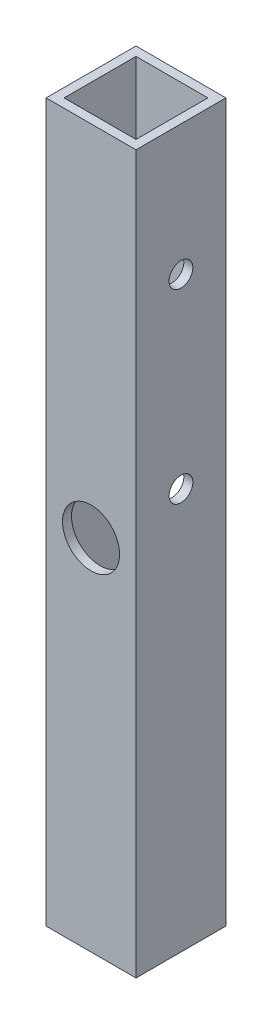
SolidWorks part; units mm, degrees
material "5052-H34"
ref_plane "Front Plane" through (0, 0, 0) normal (0, 0, 1) x (1, 0, 0)
ref_plane "Top Plane" through (0, 0, 0) normal (0, 1, 0) x (1, 0, 0)
ref_plane "Right Plane" through (0, 0, 0) normal (1, 0, 0) x (0, 0, -1)
sketch "Sketch1" plane through (0, 0, 0) normal (0, 0, 1) x (1, 0, 0)
  line L1 (-10, -79.8) -> (10, -79.8)
  line L2 (-10, -79.8) -> (-10, 79.8)
  line L3 (-10, 79.8) -> (10, 79.8)
  line L4 (10, -79.8) -> (10, 79.8)
  point P4 (10, 0)
  point P6 (0, 79.8)
  dimension "D1" = 159.6
  dimension "D2" = 20
extrude "Boss-Extrude1" add sketch "Sketch1" along normal blind 2
ref_plane "Plane1" through (-10, 79.8, 2) normal (0, -1, 0) x (-1, 0, 0)
sketch "Sketch4" plane through (0, 79.8, 0) normal (0, 1, 0) x (1, 0, 0)
  line L0 (10, -2) -> (10, 0) construction
  line L2 (-10, -2) -> (-10, -20)
  line L3 (-10, -20) -> (10, -20)
  line L4 (10, -2) -> (10, -20)
  line L5 (10, 0) -> (-10, 0) construction
  line L6 (10, -2) -> (-10, -2) construction
  line L7 (-8, -2) -> (8, -2)
  line L8 (-8, -2) -> (-8, -18)
  line L9 (-8, -18) -> (8, -18)
  line L10 (8, -2) -> (8, -18)
  line L11 (-10, -2) -> (-8, -2)
  line L12 (8, -2) -> (10, -2)
  line M9 (-10, -2) -> (10, -2)
  dimension "D1" = 0
  dimension "D2" = 20
  dimension "D3" = 2
  dimension "D4" = 2
  dimension "D5" = 2
extrude "Boss-Extrude2" add sketch "Sketch4" against normal up to surface (159.6 mm away) contours L10 L9 L8 L2 L3 L4 M9 up to face at (0, -79.8, 1)
sketch "Sketch3" plane through (0, 0, 0) normal (0, 0, -1) x (-1, 0, 0)
  line L0 (0, 79.8) -> (0, -79.8) construction
  line L1 (-33.89, 79.8) -> (53.89, 79.8) construction
  line L2 (10, -79.8) -> (-10, -79.8) construction
  circle A0 centre (0, 0) radius 6.35
  dimension "D1" = 12.7
extrude "Cut-Extrude1" cut sketch "Sketch3" against normal through all both and the other way through all
sketch "Sketch5" plane through (10, 0, 0) normal (1, 0, 0) x (0, 0, -1)
  circle A0 centre (-10, 50.8) radius 2.65 construction
  circle A1 centre (-10, 50.8) radius 2.65
  circle A2 centre (-10, 9.4343) radius 2.65
  circle A3 centre (-10, 9.4343) radius 2.65 construction
extrude "Cut-Extrude2" cut sketch "Sketch5" against normal through all both and the other way through all
